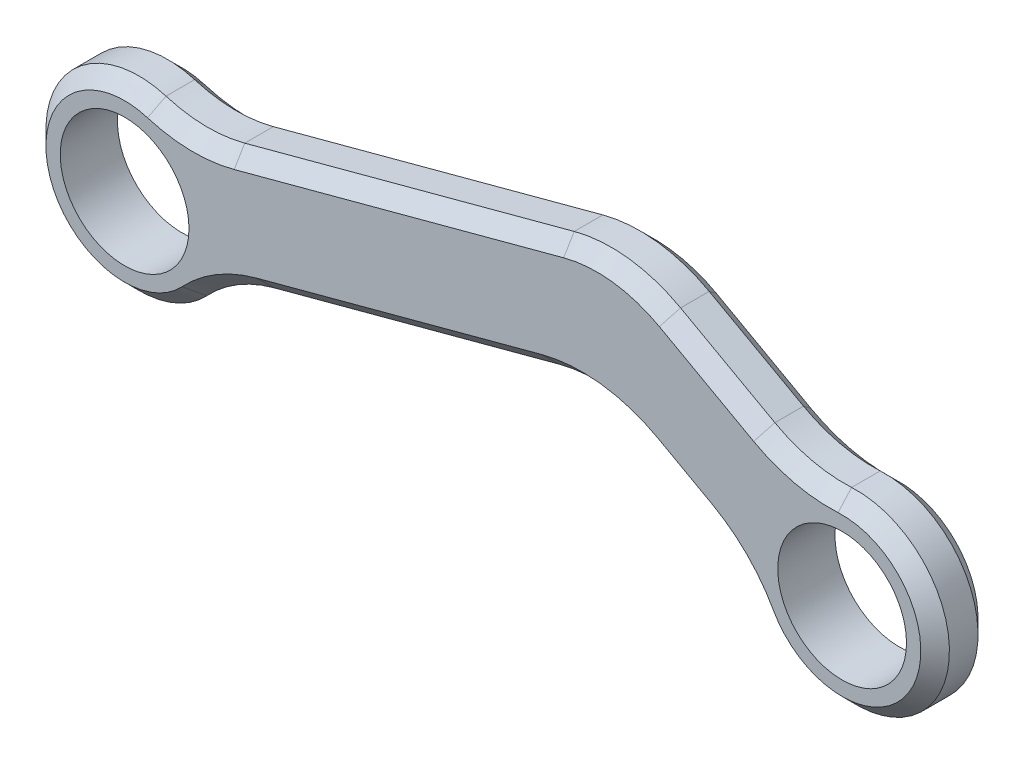
SolidWorks part; units mm, degrees
ref_plane "Front Plane" through (0, 0, 0) normal (0, 0, 1) x (1, 0, 0)
ref_plane "Top Plane" through (0, 0, 0) normal (0, 1, 0) x (1, 0, 0)
ref_plane "Right Plane" through (0, 0, 0) normal (1, 0, 0) x (0, 0, -1)
sketch "Sketch1" plane through (0, 0, 0) normal (0, 0, 1) x (1, 0, 0)
  line L7 (0, 0) -> (50.16, 0) construction
  line L9 (0, 0) -> (33.8074, 9.0587) construction
  line L10 (33.8074, 9.0587) -> (50.16, 0) construction
  line L11 (5.9842, -2.5377) -> (33.2822, 4.7768)
  line L12 (33.2822, 4.7768) -> (43.7399, -1.0163)
  line L13 (1.0353, -3.8637) -> (33.2822, 4.7768) construction
  line L14 (34.3326, 13.3405) -> (47.6165, 5.9817)
  line L15 (3.9136, 5.1898) -> (34.3326, 13.3405)
  line L16 (-1.0353, 3.8637) -> (34.3326, 13.3405) construction
  line L18 (34.3326, 13.3405) -> (52.0983, 3.499) construction
  line L19 (33.2822, 4.7768) -> (48.2217, -3.499) construction
  circle A0 centre (0, 0) radius 4.5
  circle A3 centre (50.16, 0) radius 4.5
  arc A4 (3.9136, 5.1898) -> (5.9842, -2.5377) centre (0, 0) ccw
  arc A5 (43.7399, -1.0163) -> (47.6165, 5.9817) centre (50.16, 0) ccw
  point P8 (16.0089, 10.0835)
  point P11 (0, 0)
  point P18 (18.0853, 10.7284)
  point P19 (19.9211, 11.421)
  point P20 (27.5545, 20.6502)
  dimension "D1" = 9
  dimension "D2" = 13
  dimension "D6" = 9
  dimension "D7" = 4
  dimension "D3" = 15
  dimension "D4" = 50.16
  dimension "D5" = 35
  dimension "D8" = 4
extrude "Boss-Extrude1" add sketch "Sketch1" along normal blind 4
fillet "Fillet1" radius 10 6 edges at (33.2822, 4.7768, 2) (5.9842, -2.5377, 2) (34.3326, 13.3405, 2) (47.6165, 5.9817, 2) (43.7399, -1.0163, 2) (3.9136, 5.1898, 2)
chamfer "Chamfer2" distance 1 angle 45 24 edges at (55.8459, -3.1497, 0) (-6.2785, -1.6823, 0) (55.8459, -3.1497, 4) (-6.2785, -1.6823, 4) (38.6992, 1.7761, 4) (42.8038, -0.9392, 4) (47.0547, 6.7345, 4) (41.1626, 9.5569, 4) (19.4255, 1.0639, 4) (6.9112, -2.6891, 4) (4.6407, 5.7845, 4) (18.9154, 9.2095, 4) (33.1867, 3.9979, 4) (34.237, 12.5616, 4) (33.1867, 3.9979, 0) (19.4255, 1.0639, 0) (38.6992, 1.7761, 0) (6.9112, -2.6891, 0) (42.8038, -0.9392, 0) (4.6407, 5.7845, 0) (47.0547, 6.7345, 0) (18.9154, 9.2095, 0) (41.1626, 9.5569, 0) (34.237, 12.5616, 0)
